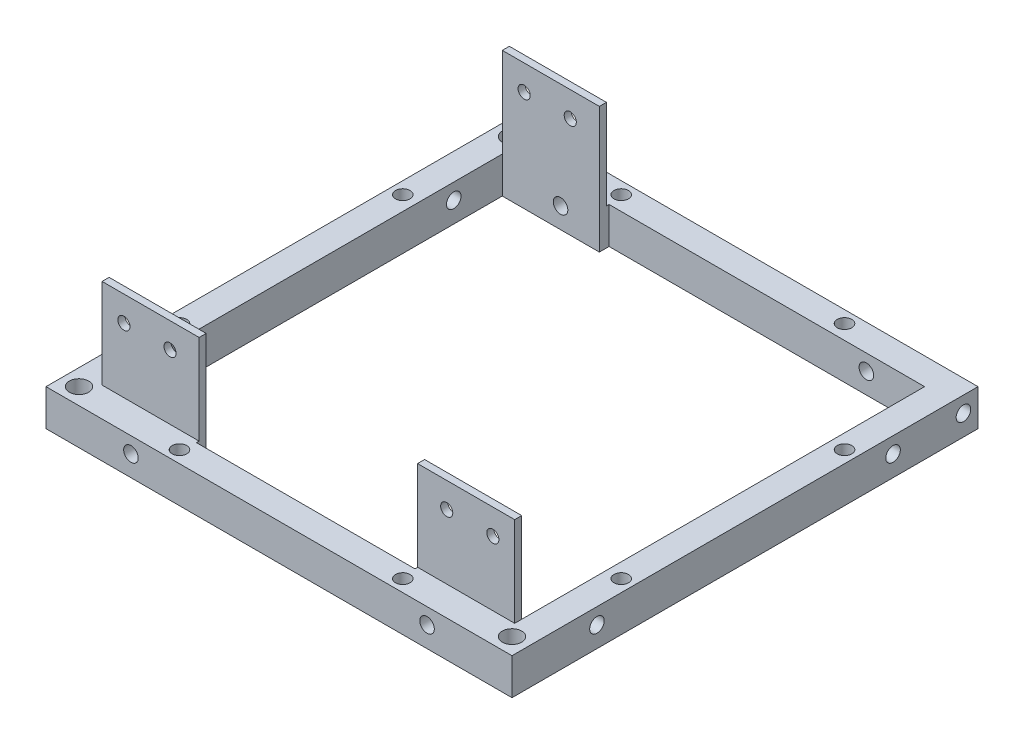
SolidWorks part; units mm, degrees
material "Aluminum"
ref_plane "Front Plane" through (0, 0, 0) normal (0, 0, 1) x (1, 0, 0)
ref_plane "Top Plane" through (0, 0, 0) normal (0, 1, 0) x (1, 0, 0)
ref_plane "Right Plane" through (0, 0, 0) normal (1, 0, 0) x (0, 0, -1)
sketch "Sketch1" plane through (0, 0, 0) normal (0, 1, 0) x (1, 0, 0)
  line L1 (48, -48) -> (-48, -48)
  line L2 (48, -48) -> (48, 48)
  line L3 (48, 48) -> (-48, 48)
  line L4 (-48, -48) -> (-48, 48)
  line L5 (48, -48) -> (-48, 48) construction
  line L6 (48, 48) -> (-48, -48) construction
  line L7 (40, -40) -> (-40, -40)
  line L8 (40, -40) -> (40, 40)
  line L9 (40, 40) -> (-40, 40)
  line L10 (-40, -40) -> (-40, 40)
  line L11 (40, -40) -> (-40, 40) construction
  line L12 (40, 40) -> (-40, -40) construction
  point P0 (0, 0)
  point P6 (0, 0)
  dimension "D1" = 96
  dimension "D2" = 96
  dimension "D3" = 8
extrude "Boss-Extrude1" add sketch "Sketch1" along normal blind 8
sketch "Sketch27" plane through (0, 8, 0) normal (0, 1, 0) x (1, 0, 0)
  line L0 (-40, 40) -> (-40, -40) construction
  line L1 (41, -41) -> (-41, -41)
  line L2 (41, -41) -> (41, 41)
  line L3 (41, 41) -> (-41, 41)
  line L4 (-41, -41) -> (-41, 41)
  line L5 (41, -41) -> (-41, 41) construction
  line L6 (41, 41) -> (-41, -41) construction
  line L7 (40, 40) -> (-40, 40) construction
  point P0 (0, 0)
  dimension "D1" = 1
  dimension "D2" = 1
extrude "Cut-Extrude2" cut sketch "Sketch27" against normal blind 10
hole_wizard "Ø3.0 (3) Diameter Hole1" positions "Sketch30" profile "Sketch29" hole size "Ø3.0" standard "ANSI Metric" end condition through all
sketch "Sketch30" plane through (0, 0, 48) normal (0, 0, 1) x (1, 0, 0)
  point P0 (-30.5, 3.25)
  point P4 (30.5, 3.25)
sketch "Sketch29" plane through (-30.5, 3.25, 48) normal (1, 0, 0) x (0, -1, 0)
  line L0 (0, 0) -> (0, 96)
  line L1 (0, 96) -> (1.5, 96)
  line L2 (1.5, 96) -> (1.5, 0)
  line L5 (1.5, 0) -> (0, 0)
  line L11 (0, -6.35) -> (0, 107.95) construction
  dimension "Thru Hole Dia." = 3
  dimension "Thru Hole Depth" = 96
hole_wizard "Tap Drill for M3x0.5 Tap2" positions "Sketch37" profile "Sketch36" hole size "M3x0.5" standard "ANSI Metric" end condition through all
sketch "Sketch37" plane through (0, 0, 0) normal (0, -1, 0) x (-1, 0, 0)
  point P0 (23, -45.5)
  point P2 (-23, -45.5)
  point P4 (-45.5, -23)
  point P6 (-45.5, 23)
  point P8 (-23, 45.5)
  point P10 (23, 45.5)
  point P12 (45.5, 23)
  point P14 (45.5, -23)
sketch "Sketch36" plane through (-23, 0, 45.5) normal (1, 0, 0) x (0, 0, -1)
  line L0 (0, 0) -> (0, 8)
  line L1 (0, 8) -> (1.5, 8)
  line L2 (1.5, 8) -> (1.5, 0)
  line L5 (1.5, 0) -> (0, 0)
  line L11 (0, -6.35) -> (0, 107.95) construction
  dimension "Thru Hole Dia." = 3
  dimension "Thru Hole Depth" = 8
sketch "Sketch38" plane through (0, 8, 0) normal (0, 1, 0) x (1, 0, 0)
  line L0 (48, 48) -> (-48, 48) construction
  line L1 (42.5, -42.5) -> (-42.5, -42.5)
  line L2 (42.5, -42.5) -> (42.5, 42.5)
  line L3 (42.5, 42.5) -> (-42.5, 42.5)
  line L4 (-42.5, -42.5) -> (-42.5, 42.5)
  line L5 (42.5, -42.5) -> (-42.5, 42.5) construction
  line L6 (42.5, 42.5) -> (-42.5, -42.5) construction
  line L7 (-48, 48) -> (-48, -48) construction
  point P0 (0, 0)
  dimension "D1" = 5.5
  dimension "D2" = 5.5
extrude "Cut-Extrude4" cut sketch "Sketch38" against normal blind 10
hole_wizard "Ø3.0 (3) Diameter Hole7" positions "Sketch40" profile "Sketch41" hole size "Ø3.0" standard "ISO" end condition through all
sketch "Sketch40" plane through (-48, 0, 0) normal (-1, 0, 0) x (0, 0, 1)
  line L0 (0, 0) -> (0, 8) construction
  line L1 (-48, 0) -> (48, 0) construction
  line L2 (-48, 8) -> (48, 8) construction
  point P0 (-30.5, 3.25)
  point P2 (30.5, 3.25)
sketch "Sketch41" plane through (-48, 3.25, -30.5) normal (0, 1, 0) x (0, 0, 1)
  line L0 (0, 0) -> (0, 96)
  line L1 (0, 96) -> (1.5, 96)
  line L2 (1.5, 96) -> (1.5, 0)
  line L5 (1.5, 0) -> (0, 0)
  line L11 (0, -6.35) -> (0, 107.95) construction
  dimension "Thru Hole Dia." = 3
  dimension "Thru Hole Depth" = 96
sketch "Sketch44" plane through (0, 0, 0) normal (0, -1, 0) x (1, 0, 0)
  line L0 (42.5, -42.5) -> (-42.5, -42.5) construction
  line L1 (42.5, -42.5) -> (38.5, -42.5)
  line L2 (42.5, -42.5) -> (42.5, -38.5)
  line L3 (42.5, -38.5) -> (38.5, -38.5)
  line L4 (38.5, -42.5) -> (38.5, -38.5)
  line L5 (42.5, 42.5) -> (42.5, -42.5) construction
  line L6 (0, 0) -> (0, -67.1068) construction
  line L7 (0, 0) -> (66.4168, 0) construction
  line L8 (-38.5, -42.5) -> (-38.5, -38.5)
  line L9 (-42.5, -38.5) -> (-38.5, -38.5)
  line L10 (-42.5, -42.5) -> (-42.5, -38.5)
  line L11 (-42.5, -42.5) -> (-38.5, -42.5)
  line L12 (-42.5, 42.5) -> (-38.5, 42.5)
  line L13 (-42.5, 42.5) -> (-42.5, 38.5)
  line L14 (-42.5, 38.5) -> (-38.5, 38.5)
  line L15 (-38.5, 42.5) -> (-38.5, 38.5)
  line L16 (38.5, 42.5) -> (38.5, 38.5)
  line L17 (42.5, 38.5) -> (38.5, 38.5)
  line L18 (42.5, 42.5) -> (42.5, 38.5)
  line L19 (42.5, 42.5) -> (38.5, 42.5)
  dimension "D1" = 4
  dimension "D2" = 4
extrude "Boss-Extrude2" add sketch "Sketch44" against normal blind 8
sketch "Sketch45" plane through (0, 8, 0) normal (0, 1, 0) x (1, 0, 0)
  line L1 (-42.5, 38.5) -> (-38.5, 38.5)
  line L2 (-42.5, 38.5) -> (-42.5, 35)
  line L3 (-42.5, 35) -> (-38.5, 35)
  line L4 (-38.5, 38.5) -> (-38.5, 35)
  dimension "D1" = 4
  dimension "D2" = 3.5
extrude "Boss-Extrude3" add sketch "Sketch45" against normal blind 8
sketch "Sketch49" plane through (48, 0, 0) normal (1, 0, 0) x (0, 0, -1)
  line L0 (48, 8) -> (48, 0) construction
  line L1 (-48, 8) -> (48, 8)
  line L2 (-48, 8) -> (-48, 6.5)
  line L3 (-48, 6.5) -> (48, 6.5)
  line L4 (48, 8) -> (48, 6.5)
  dimension "D1" = 1.5
extrude "Cut-Extrude5" cut sketch "Sketch49" against normal blind 146
hole_wizard "Tap Drill for M4 Tap1" positions "Sketch51" profile "Sketch50" hole size "M4" standard "ISO" end condition through all
sketch "Sketch51" plane through (0, 6.5, 0) normal (0, 1, 0) x (1, 0, 0)
  line L1 (-48, -48) -> (48, -48) construction
  line L2 (48, -48) -> (48, 48) construction
  line L3 (-48, -48) -> (-48, 48) construction
  line L4 (-48, 48) -> (48, 48) construction
  point P0 (44.6, -44.6)
  point P4 (-44.6, -44.6)
  point P6 (-44.6, 44.6)
  dimension "D1" = 3.4
  dimension "D2" = 3.4
  dimension "D3" = 3.4
  dimension "D4" = 3.4
  dimension "D5" = 3.4
  dimension "D6" = 3.4
sketch "Sketch50" plane through (44.6, 6.5, 44.6) normal (1, 0, 0) x (0, 0, 1)
  line L0 (0, 0) -> (0, 6.5)
  line L1 (0, 6.5) -> (2, 6.5)
  line L2 (2, 6.5) -> (2, 0)
  line L5 (2, 0) -> (0, 0)
  line L11 (0, -6.35) -> (0, 107.95) construction
  dimension "Thru Hole Dia." = 4
  dimension "Thru Hole Depth" = 6.5
sketch "Sketch53" plane through (-38.5, 0, 0) normal (1, 0, 0) x (0, 0, -1)
  line L1 (-42.5, 6.5) -> (-38.5, 6.5)
  line L2 (-42.5, 6.5) -> (-42.5, 0)
  line L3 (-42.5, 0) -> (-38.5, 0)
  line L4 (-38.5, 6.5) -> (-38.5, 0)
extrude "Boss-Extrude5" add sketch "Sketch53" along normal blind 78
sketch "Sketch54" plane through (0, 6.5, 0) normal (0, 1, 0) x (1, 0, 0)
  line L0 (42.5, -38.5) -> (-42.5, -38.5) construction
  line L1 (-42.5, 35) -> (-42.5, -38.5) construction
  line L3 (-42.5, -40.5) -> (-42.5, -41.95)
  line L6 (0, -38.5) -> (0, -84.4574) construction
  line L7 (-22.5, -40.5) -> (-22.5, -41.95)
  line L8 (-42.5, -41.95) -> (-22.5, -41.95)
  line L10 (-42.5, -40.5) -> (-22.5, -40.5)
  line L11 (0, 0) -> (25.8217, 0) construction
  dimension "D1" = 1.45
  dimension "D2" = 2
  dimension "D3" = 20
  dimension "D4" = 0
  dimension "D5" = 20
  dimension "D6" = 1.45
sketch "Sketch57" plane through (0, 0, -35) normal (0, 0, 1) x (1, 0, 0)
  line L1 (-42.5, 6.5) -> (-38.5, 6.5)
  line L2 (-42.5, 6.5) -> (-42.5, 0)
  line L3 (-42.5, 0) -> (-38.5, 0)
  line L4 (-38.5, 6.5) -> (-38.5, 0)
extrude "Cut-Extrude6" cut sketch "Sketch57" against normal blind 7.5
sketch "Sketch58" plane through (38.5, 0, 0) normal (-1, 0, 0) x (0, 0, 1)
  line L1 (-42.5, 6.5) -> (-38.5, 6.5)
  line L2 (-42.5, 6.5) -> (-42.5, 0)
  line L3 (-42.5, 0) -> (-38.5, 0)
  line L4 (-38.5, 6.5) -> (-38.5, 0)
extrude "Boss-Extrude7" add sketch "Sketch58" along normal blind 81
sketch "Sketch61" plane through (0, 6.5, 0) normal (0, 1, 0) x (1, 0, 0)
  line L0 (-48, 48) -> (48, 48) construction
  line L1 (-16, 42.5) -> (16, 42.5)
  line L2 (-16, 42.5) -> (-16, -42.5)
  line L3 (-16, -42.5) -> (16, -42.5)
  line L4 (16, 42.5) -> (16, -42.5)
  line L5 (-48, -48) -> (48, -48) construction
  dimension "D1" = 5.5
  dimension "D2" = 5.5
  dimension "D3" = 16
  dimension "D4" = 16
extrude "Cut-Extrude7" cut sketch "Sketch61" against normal blind 81
sketch "Sketch66" plane through (0, 6.5, 0) normal (0, 1, 0) x (1, 0, 0)
  line L0 (42.5, -38.5) -> (42.5, 38.5) construction
  line L1 (42.5, 40.099) -> (-42.5, 40.099)
  line L2 (42.5, 40.099) -> (42.5, -40.099)
  line L3 (42.5, -40.099) -> (-42.5, -40.099)
  line L4 (-42.5, 40.099) -> (-42.5, -40.099)
  line L5 (-42.5, 38.5) -> (-42.5, -38.5) construction
extrude "Cut-Extrude8" cut sketch "Sketch66" against normal blind 10
sketch "Sketch67" plane through (0, 0, 0) normal (0, -1, 0) x (1, 0, 0)
  line L0 (42.5, 40.099) -> (42.5, -40.099) construction
  line L1 (-42.5, 42.5) -> (42.5, 42.5)
  line L2 (-42.5, 42.5) -> (-42.5, -42.5)
  line L3 (-42.5, -42.5) -> (42.5, -42.5)
  line L4 (42.5, 42.5) -> (42.5, -42.5)
  line L5 (-16, 42.5) -> (16, 42.5) construction
  line L6 (-42.5, -40.099) -> (-42.5, 40.099) construction
  line L7 (16, -42.5) -> (-16, -42.5) construction
extrude "Cut-Extrude9" cut sketch "Sketch67" against normal blind 3.5
sketch "Sketch68" plane through (0, 6.5, 0) normal (0, 1, 0) x (1, 0, 0)
  line L1 (26, 42.5) -> (-26, 42.5)
  line L2 (26, 42.5) -> (26, -42.5)
  line L3 (26, -42.5) -> (-26, -42.5)
  line L4 (-26, 42.5) -> (-26, -42.5)
  line L5 (0, 0) -> (0, 30.6776) construction
  line L6 (16, 42.5) -> (-16, 42.5) construction
  dimension "D1" = 26
  dimension "D2" = 26
extrude "Cut-Extrude10" cut sketch "Sketch68" against normal blind 56
extrude "Boss-Extrude8" add sketch "Sketch54" along normal blind 18.5
mirror "Mirror1" about plane through (0, 0, 0) normal (1, 0, 0) of "Boss-Extrude8"
sketch "Sketch75" plane through (26, 0, 0) normal (-1, 0, 0) x (0, 0, 1)
  line L1 (40.099, 6.5) -> (42.5, 6.5)
  line L2 (40.099, 6.5) -> (40.099, 3.5)
  line L3 (40.099, 3.5) -> (42.5, 3.5)
  line L4 (42.5, 6.5) -> (42.5, 3.5)
extrude "Cut-Extrude12" cut sketch "Sketch75" against normal blind 10.22 and the other way blind 62.22
mirror "Mirror2" about plane through (0, 0, 0) normal (0, 0, 1) of "Boss-Extrude8"
mirror "Mirror3" about plane through (0, 0, 0) normal (0, 0, 1) of "Cut-Extrude12"
sketch "Sketch77" plane through (36.22, 0, 0) normal (-1, 0, 0) x (0, 0, 1)
  line L1 (-42.5, 6.5) -> (-40.099, 6.5)
  line L2 (-42.5, 6.5) -> (-42.5, 3.5)
  line L3 (-42.5, 3.5) -> (-40.099, 3.5)
  line L4 (-40.099, 6.5) -> (-40.099, 3.5)
extrude "Cut-Extrude13" cut sketch "Sketch77" against normal blind 6.28
sketch "Sketch78" plane through (0, 0, 0) normal (0, -1, 0) x (1, 0, 0)
  line L1 (-42.5, 42.5) -> (42.5, 42.5)
  line L2 (-42.5, 42.5) -> (-42.5, -42.5)
  line L3 (-42.5, -42.5) -> (42.5, -42.5)
  line L4 (42.5, 42.5) -> (42.5, -42.5)
extrude "Cut-Extrude14" cut sketch "Sketch78" against normal blind 6.5
sketch "Sketch79" plane through (0, 0, 0) normal (0, -1, 0) x (1, 0, 0)
  line L0 (40.5, -40.5) -> (40.5, 40.5)
  line L1 (42.5, -42.5) -> (-42.5, -42.5)
  line L2 (42.5, -42.5) -> (42.5, 42.5)
  line L3 (42.5, 42.5) -> (-42.5, 42.5)
  line L4 (-42.5, -42.5) -> (-42.5, 42.5)
  line L5 (40.5, 40.5) -> (-40.5, 40.5)
  line L6 (-40.5, -40.5) -> (-40.5, 40.5)
  line L7 (40.5, -40.5) -> (-40.5, -40.5)
  dimension "D1" = 2
extrude "Boss-Extrude12" add sketch "Sketch79" against normal blind 6.5
hole_wizard "Tap Drill for M2.5x0.45 Tap2" positions "Sketch83" profile "Sketch82" hole size "M2.5x0.45" standard "ANSI Metric" end condition through all
sketch "Sketch83" plane through (0, 0, 40.5) normal (0, 0, -1) x (-1, 0, 0)
  line L0 (42.5, 25) -> (42.5, 6.5) construction
  line L3 (-42.5, 25) -> (-42.5, 6.5) construction
  point P0 (28.5, 19.7992)
  point P3 (38, 19.7992)
  point P6 (-38, 19.7992)
  point P9 (-28.5, 19.7992)
  dimension "D1" = 4.5
  dimension "D2" = 9.5
  dimension "D7" = 4.5
  dimension "D8" = 9.5
sketch "Sketch82" plane through (-28.5, 19.7992, 40.5) normal (1, 0, 0) x (0, 1, 0)
  line L0 (0, 0) -> (0, 7.5)
  line L1 (0, 7.5) -> (1.25, 7.5)
  line L2 (1.25, 7.5) -> (1.25, 0)
  line L5 (1.25, 0) -> (0, 0)
  line L11 (0, -6.35) -> (0, 107.95) construction
  dimension "Thru Hole Dia." = 2.5
  dimension "Thru Hole Depth" = 7.5
hole_wizard "Tap Drill for M2.5x0.45 Tap3" positions "Sketch85" profile "Sketch84" hole size "M2.5x0.45" standard "ANSI Metric" end condition up to next
sketch "Sketch85" plane through (0, 0, -40.5) normal (0, 0, 1) x (1, 0, 0)
  point P0 (-28.5, 19.7992)
  point P3 (-38, 19.7992)
sketch "Sketch84" plane through (-28.5, 19.7992, -40.5) normal (1, 0, 0) x (0, -1, 0)
  line L0 (0, 0) -> (0, 1.451)
  line L1 (0, 1.451) -> (1.25, 1.451)
  line L2 (1.25, 1.451) -> (1.25, 0)
  line L5 (1.25, 0) -> (0, 0)
  line L11 (0, -6.35) -> (0, 107.95) construction
  dimension "Thru Hole Dia." = 2.5
  dimension "Thru Hole Depth" = 1.451
hole_wizard "Tap Drill for M3x0.5 Tap4" positions "Sketch87" profile "Sketch86" hole size "M3x0.5" standard "ANSI Metric"
sketch "Sketch87" plane through (48, 0, 0) normal (1, 0, 0) x (0, 0, -1)
  line L0 (-48, 6.5) -> (48, 6.5) construction
  point P0 (45, 3.25)
  dimension "D1" = 3.25
sketch "Sketch86" plane through (48, 3.25, -45) normal (0, 1, 0) x (0, 0, -1)
  line L0 (0, 0) -> (0, 7.5)
  line L1 (0, 7.5) -> (1.5, 7.5)
  line L2 (1.5, 7.5) -> (1.5, 0)
  line L5 (1.5, 0) -> (0, 0)
  line L10 (0, 7.5) -> (-1.5, 7.5) construction
  line L11 (0, -6.35) -> (0, 107.95) construction
  dimension "Hole Dia." = 3
  dimension "Hole Depth" = 7.5
  dimension "Drill Angle" = 180
sketch "Sketch88" plane through (0, 6.5, 0) normal (0, 1, 0) x (1, 0, 0)
  line L0 (40.5, 40.5) -> (40.5, -40.5) construction
  line L1 (40.5, 35) -> (42.5, 35)
  line L2 (40.5, 35) -> (40.5, -35)
  line L3 (40.5, -35) -> (42.5, -35)
  line L4 (42.5, 35) -> (42.5, -35)
  line L5 (-40.5, 40.5) -> (40.5, 40.5) construction
  line L6 (40.5, -40.5) -> (-40.5, -40.5) construction
  line L7 (-40.5, -40.5) -> (-40.5, 40.5) construction
  line L8 (35, -40.5) -> (-35, -40.5)
  line L9 (35, -40.5) -> (35, -42.5)
  line L10 (35, -42.5) -> (-35, -42.5)
  line L11 (-35, -40.5) -> (-35, -42.5)
  line L13 (-40.5, -35) -> (-42.5, -35)
  line L14 (-40.5, -35) -> (-40.5, 35)
  line L15 (-40.5, 35) -> (-42.5, 35)
  line L16 (-42.5, -35) -> (-42.5, 35)
  line L17 (35, 40.5) -> (-35, 40.5)
  line L18 (35, 40.5) -> (35, 42.5)
  line L19 (35, 42.5) -> (-35, 42.5)
  line L20 (-35, 40.5) -> (-35, 42.5)
  dimension "D1" = 5.5
  dimension "D2" = 5.5
  dimension "D3" = 2
  dimension "D4" = 2
  dimension "D5" = 5.5
  dimension "D6" = 5.5
  dimension "D7" = 5.5
  dimension "D8" = 5.5
  dimension "D9" = 2
  dimension "D10" = 2
  dimension "D11" = 5.5
  dimension "D12" = 5.5
extrude "Cut-Extrude15" cut sketch "Sketch88" against normal blind 10
sketch "Sketch89" plane through (0, 6.5, 0) normal (0, 1, 0) x (1, 0, 0)
  line L0 (-22.5, 40.5) -> (-42.5, 40.5) construction
  line L1 (-42.5, 40.5) -> (42.5, 40.5)
  line L2 (-42.5, 40.5) -> (-42.5, -40.5)
  line L3 (-42.5, -40.5) -> (42.5, -40.5)
  line L4 (42.5, 40.5) -> (42.5, -40.5)
  line L5 (22.5, -40.5) -> (42.5, -40.5) construction
extrude "Cut-Extrude16" cut sketch "Sketch89" against normal blind 10
sketch "Sketch90" plane through (35, 0, 0) normal (-1, 0, 0) x (0, 0, 1)
  line L1 (-42.5, 0) -> (-40.5, 0)
  line L2 (-42.5, 0) -> (-42.5, 6.5)
  line L3 (-42.5, 6.5) -> (-40.5, 6.5)
  line L4 (-40.5, 0) -> (-40.5, 6.5)
extrude "Cut-Extrude17" cut sketch "Sketch90" against normal blind 7.5
sketch "Sketch91" plane through (0, 0, 0) normal (0, -1, 0) x (1, 0, 0)
  line L1 (-48, 48) -> (48, 48)
  line L2 (-48, 48) -> (-48, -48)
  line L3 (-48, -48) -> (48, -48)
  line L4 (48, 48) -> (48, -48)
  line L5 (42.5, -42.5) -> (-35, -42.5)
  line L6 (42.5, -42.5) -> (42.5, 40.5)
  line L7 (35, 42.5) -> (-35, 42.5)
  line L8 (-42.5, -40.5) -> (-42.5, 40.5)
  line L9 (-35, 40.5) -> (-42.5, 40.5)
  line L10 (-35, 40.5) -> (-35, 42.5)
  line L13 (35, 40.5) -> (42.5, 40.5)
  line L14 (35, 40.5) -> (35, 42.5)
  line L19 (-42.5, -40.5) -> (-35, -40.5)
  line L20 (-35, -42.5) -> (-35, -40.5)
  circle A0 centre (23, -45.5) radius 1.5
  circle A1 centre (-23, -45.5) radius 1.5
  circle A2 centre (44.6, 44.6) radius 2
  circle A3 centre (-45.5, -23) radius 1.5
  circle A4 centre (-45.5, 23) radius 1.5
  circle A5 centre (-23, 45.5) radius 1.5
  circle A6 centre (23, 45.5) radius 1.5
  circle A7 centre (45.5, 23) radius 1.5
  circle A8 centre (-44.6, -44.6) radius 2
  circle A9 centre (45.5, -23) radius 1.5
  circle A10 centre (-44.6, 44.6) radius 2
  dimension "D1" = 3
  dimension "D2" = 3
  dimension "D3" = 3
  dimension "D4" = 3
  dimension "D5" = 3
  dimension "D6" = 3
  dimension "D7" = 3
  dimension "D8" = 3
extrude "Boss-Extrude14" add sketch "Sketch91" along normal blind 1
sketch "Sketch92" plane through (0, 6.5, 0) normal (0, -1, 0) x (1, 0, 0)
  line L1 (-22.5, 40.5) -> (-35, 40.5)
  line L2 (-22.5, 40.5) -> (-22.5, 42.5)
  line L3 (-22.5, 42.5) -> (-35, 42.5)
  line L4 (-35, 40.5) -> (-35, 42.5)
extrude "Boss-Extrude15" add sketch "Sketch92" along normal blind 1
sketch "Sketch94" plane through (0, 6.5, 0) normal (0, -1, 0) x (1, 0, 0)
  line L0 (-22.5, 42.5) -> (35, 42.5) construction
  line L1 (35, 40.5) -> (22.5, 40.5)
  line L2 (35, 40.5) -> (35, 42.5)
  line L3 (35, 42.5) -> (22.5, 42.5)
  line L4 (22.5, 40.5) -> (22.5, 42.5)
extrude "Boss-Extrude16" add sketch "Sketch94" along normal blind 1
sketch "Sketch95" plane through (0, 6.5, 0) normal (0, -1, 0) x (1, 0, 0)
  line L1 (-22.5, -40.5) -> (-35, -40.5)
  line L2 (-22.5, -40.5) -> (-22.5, -42.5)
  line L3 (-22.5, -42.5) -> (-35, -42.5)
  line L4 (-35, -40.5) -> (-35, -42.5)
extrude "Boss-Extrude17" add sketch "Sketch95" along normal blind 1
sketch "Sketch96" plane through (0, 0, -42.5) normal (0, 0, 1) x (1, 0, 0)
  line L1 (-22.5, 5.5) -> (-35, 5.5)
  line L2 (-22.5, 5.5) -> (-22.5, -1)
  line L3 (-22.5, -1) -> (-35, -1)
  line L4 (-35, 5.5) -> (-35, -1)
  circle A0 centre (-30.5, 3.25) radius 1.5
extrude "Boss-Extrude18" add sketch "Sketch96" along normal blind 2
sketch "Sketch97" plane through (0, 0, 42.5) normal (0, 0, -1) x (-1, 0, 0)
  line L1 (-22.5, 5.5) -> (-35, 5.5)
  line L2 (-22.5, 5.5) -> (-22.5, -1)
  line L3 (-22.5, -1) -> (-35, -1)
  line L4 (-35, 5.5) -> (-35, -1)
  line L5 (22.5, 5.5) -> (35, 5.5)
  line L6 (22.5, 5.5) -> (22.5, -1)
  line L7 (22.5, -1) -> (35, -1)
  line L8 (35, 5.5) -> (35, -1)
  circle A0 centre (30.5, 3.25) radius 1.5
  circle A1 centre (-30.5, 3.25) radius 1.5
extrude "Boss-Extrude19" add sketch "Sketch97" along normal blind 2
